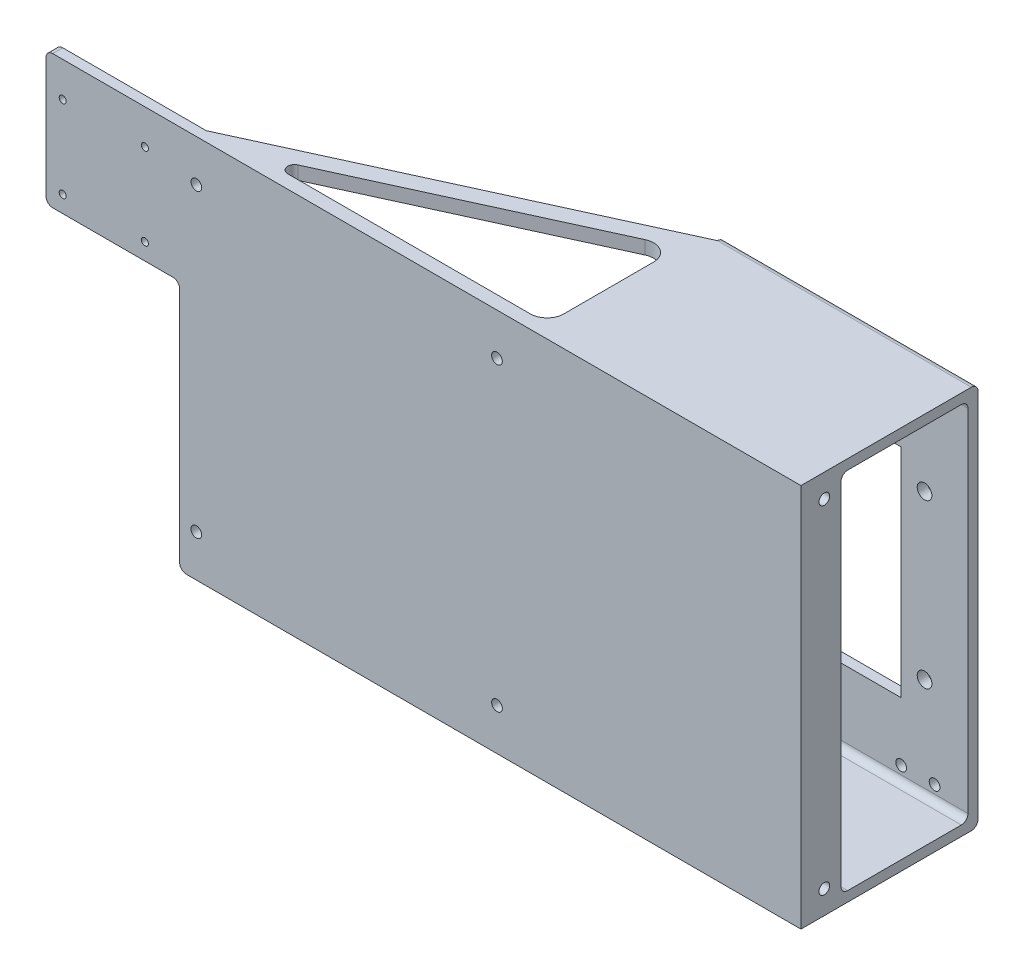
SolidWorks part; units mm, degrees
ref_plane "前视基准面" through (0, 0, 0) normal (0, 0, 1) x (1, 0, 0)
ref_plane "上视基准面" through (0, 0, 0) normal (0, 1, 0) x (1, 0, 0)
ref_plane "右视基准面" through (0, 0, 0) normal (1, 0, 0) x (0, 0, -1)
sketch "草图2" plane through (0, 0, 0) normal (0, 0, 1) x (1, 0, 0)
  line L4 (37.2625, -42.4817) -> (86.0528, -91.2721) construction
  line L5 (23.0528, -9.4817) -> (99.0528, -9.4817)
  line L6 (23.0528, -9.4817) -> (23.0528, -124.4817)
  line L7 (23.0528, -124.4817) -> (99.0528, -124.4817)
  line L8 (99.0528, -9.4817) -> (99.0528, -124.4817)
  line L9 (86.0528, -42.4817) -> (37.2625, -91.2721) construction
  circle A0 centre (86.0528, -91.2721) radius 2.2
  circle A1 centre (86.0528, -42.4817) radius 2.2
  circle A2 centre (37.2625, -42.4817) radius 2.2
  circle A3 centre (37.2625, -91.2721) radius 2.2
  circle A4 centre (89.0528, -16.9817) radius 1.6
  circle A5 centre (79.0528, -16.9817) radius 1.6
  circle A6 centre (41.0528, -16.9817) radius 1.6
  circle A7 centre (51.0528, -16.9817) radius 1.6
  circle A8 centre (41.0528, -116.9817) radius 1.6
  circle A9 centre (51.0528, -116.9817) radius 1.6
  circle A10 centre (79.0528, -116.9817) radius 1.6
  circle A11 centre (89.0528, -116.9817) radius 1.6
  point P12 (64.3101, -80.4099)
  dimension "D4" = 90
  dimension "D5" = 13
  dimension "D6" = 33
  dimension "D7" = 69
  dimension "D8" = 3.2
  dimension "D3" = 69
  dimension "D9" = 10
  dimension "D10" = 7.5
  dimension "D11" = 4.4
  dimension "D12" = 4.4
  dimension "D13" = 4.4
  dimension "D14" = 4.4
  dimension "D18" = 100
  dimension "D1" = 115
  dimension "D2" = 76
  dimension "D15" = 2
  dimension "D16" = 2
  dimension "D17" = 2
extrude "凸台-拉伸1" add sketch "草图2" along normal blind 3
sketch "草图3" plane through (23.0528, 0, 0) normal (-1, 0, 0) x (0, 0, 1)
  line L0 (0, -9.4817) -> (0, -124.4817) construction
  line L1 (0, -9.4817) -> (53, -9.4817)
  line L2 (0, -9.4817) -> (0, -12.4817)
  line L3 (0, -12.4817) -> (50, -12.4817)
  line L8 (50, -12.4817) -> (50, -121.4817)
  line L9 (53, -124.4817) -> (0, -124.4817)
  line L11 (50, -121.4817) -> (0, -121.4817)
  line L12 (0, -124.4817) -> (0, -121.4817)
  line L13 (53, -124.4817) -> (53, -9.4817)
  dimension "D1" = 115
  dimension "D2" = 3
  dimension "D4" = 50
extrude "凸台-拉伸2" add sketch "草图3" against normal blind 76
sketch "草图4" plane through (23.0528, 0, 0) normal (-1, 0, 0) x (0, 0, 1)
  line L0 (3, -12.4817) -> (50, -12.4817) construction
  line L1 (3, -12.4817) -> (50, -12.4817)
  line L2 (3, -12.4817) -> (3, -121.4817)
  line L3 (3, -121.4817) -> (50, -121.4817)
  line L4 (50, -12.4817) -> (50, -121.4817)
  line L5 (3, -12.4817) -> (3, -121.4817) construction
extrude "凸台-拉伸3" add sketch "草图4" against normal blind 3
sketch "草图5" plane through (99.0528, 0, 0) normal (1, 0, 0) x (0, 0, -1)
  line L0 (-53, -124.4817) -> (0, -124.4817) construction
  line L1 (-53, -9.4817) -> (-41, -9.4817)
  line L2 (-53, -9.4817) -> (-53, -124.4817)
  line L3 (-53, -124.4817) -> (-41, -124.4817)
  line L4 (-41, -9.4817) -> (-41, -124.4817)
  circle A0 centre (-46, -117.4817) radius 1.6
  circle A1 centre (-46, -16.4817) radius 1.6
  dimension "D2" = 5
  dimension "D3" = 7
  dimension "D4" = 5
  dimension "D5" = 7
  dimension "D1" = 12
extrude "凸台-拉伸4" add sketch "草图5" against normal blind 3
fillet "圆角1" radius 2 8 edges at (97.5528, -121.4817, 41) (97.5528, -12.4817, 41) (61.0528, -12.4817, 50) (61.0528, -121.4817, 50) (62.5528, -121.4817, 3) (61.0528, -124.4817, 0) (61.0528, -9.4817, 0) (62.5528, -12.4817, 3)
sketch "草图6" plane through (23.0528, 0, 0) normal (-1, 0, 0) x (0, 0, 1)
  line L1 (53, -9.4817) -> (50, -9.4817)
  line L2 (53, -9.4817) -> (53, -124.4817)
  line L3 (53, -124.4817) -> (50, -124.4817)
  line L4 (50, -9.4817) -> (50, -124.4817)
  line L5 (53, -124.4817) -> (2, -124.4817) construction
  dimension "D1" = 3
  dimension "D2" = 115
  dimension "D3" = 0
extrude "凸台-拉伸5" add sketch "草图6" along normal blind 110
sketch "草图7" plane through (0, 0, 50) normal (0, 0, -1) x (-1, 0, 0)
  line L0 (86.9472, -9.4817) -> (86.9472, -124.4817) construction
  line L1 (86.9472, -9.4817) -> (-23.0528, -9.4817) construction
  circle A0 centre (81.9472, -21.9817) radius 1.6
  circle A1 centre (81.9472, -111.9817) radius 1.6
  circle A2 centre (-8.0528, -21.9817) radius 1.6
  circle A3 centre (-8.0528, -111.9817) radius 1.6
  point P32 (0, 0)
  point P33 (0, 0)
  dimension "D1" = 5
  dimension "D2" = 12.5
  dimension "D5" = 90
  dimension "D6" = 90
  dimension "D3" = 2
  dimension "D4" = 2
extrude "切除-拉伸1" cut sketch "草图7" against normal blind 110
sketch "草图8" plane through (0, 0, 0) normal (0, 0, -1) x (-1, 0, 0)
  line L0 (-99.0528, -122.4817) -> (-99.0528, -11.4817) construction
  line L1 (-79.0528, -34.4817) -> (-48.0528, -34.4817)
  line L2 (-79.0528, -34.4817) -> (-79.0528, -99.4817)
  line L3 (-79.0528, -99.4817) -> (-48.0528, -99.4817)
  line L4 (-48.0528, -34.4817) -> (-48.0528, -99.4817)
  line L5 (-23.0528, -11.4817) -> (-23.0528, -122.4817) construction
  line L6 (-23.0528, -11.4817) -> (-99.0528, -11.4817) construction
  line L7 (-99.0528, -122.4817) -> (-23.0528, -122.4817) construction
  dimension "D1" = 20
  dimension "D2" = 25
  dimension "D3" = 23
  dimension "D4" = 23
extrude "切除-拉伸2" cut sketch "草图8" against normal blind 3
sketch "草图9" plane through (0, -124.4817, 0) normal (0, -1, 0) x (-1, 0, 0)
  line L0 (-23.0528, -2) -> (81.9472, -50)
  line L1 (81.9472, -50) -> (-23.0528, -50)
  line L2 (-23.0528, -50) -> (-23.0528, -2)
extrude "凸台-拉伸6" add sketch "草图9" against normal blind 4
sketch "草图10" plane through (0, -9.4817, 0) normal (0, 1, 0) x (1, 0, 0)
  line L0 (23.0528, -2) -> (-81.9472, -50)
  line L1 (-81.9472, -50) -> (23.0528, -50)
  line L2 (23.0528, -50) -> (23.0528, -2)
extrude "凸台-拉伸7" add sketch "草图10" against normal blind 4
sketch "草图11" plane through (0, -124.4817, 0) normal (0, -1, 0) x (-1, 0, 0)
  line L0 (58.548, -49) -> (-14.0528, -49)
  line L1 (-19.0528, -44) -> (-19.0528, -17.1096)
  line L2 (-11.974, -12.5623) -> (59.3795, -45.1811)
  line L3 (-99.0528, -53) -> (86.9472, -53) construction
  line L4 (-99.0528, -53) -> (-99.0528, -2) construction
  line L5 (81.9472, -50) -> (-23.0528, -2) construction
  arc A0 (-14.0528, -49) -> (-19.0528, -44) centre (-14.0528, -44) cw
  arc A1 (-19.0528, -17.1096) -> (-11.974, -12.5623) centre (-14.0528, -17.1096) cw
  arc A2 (58.548, -49) -> (59.3795, -45.1811) centre (58.548, -47) ccw
  dimension "D4" = 5
  dimension "D5" = 2
  dimension "D1" = 4
  dimension "D2" = 80
  dimension "D3" = 5
extrude "切除-拉伸3" cut sketch "草图11" against normal blind 124
sketch "草图16" plane through (-86.9472, 0, 0) normal (-1, 0, 0) x (0, 0, 1)
  line L0 (53, -124.4817) -> (53, -9.4817) construction
  line L1 (50, -9.4817) -> (53, -9.4817)
  line L2 (50, -9.4817) -> (50, -49.4817)
  line L3 (50, -49.4817) -> (53, -49.4817)
  line L4 (53, -9.4817) -> (53, -49.4817)
  dimension "D1" = 40
extrude "凸台-拉伸10" add sketch "草图16" along normal blind 40
sketch "草图17" plane through (0, 0, 50) normal (0, 0, -1) x (-1, 0, 0)
  line L4 (126.9472, -9.4817) -> (126.9472, -49.4817) construction
  line L6 (126.9472, -49.4817) -> (86.9472, -49.4817) construction
  circle A4 centre (121.9472, -44.4817) radius 1.05
  circle A5 centre (121.9472, -19.8817) radius 1.05
  circle A26 centre (97.3472, -19.8817) radius 1.05
  circle A29 centre (97.3472, -44.4817) radius 1.05
  point P32 (29.0087, 124.7414)
  point P33 (29.0087, 124.7414)
  dimension "D2" = 5
  dimension "D15" = 24.6
  dimension "D16" = 2.1
  dimension "D7" = 2.1
  dimension "D8" = 2.1
  dimension "D4" = 5
  dimension "D3" = 24.6
extrude "切除-拉伸5" cut sketch "草图17" against normal blind 40
fillet "圆角5" radius 2 4 edges at (-126.9472, -9.4817, 51.5) (-126.9472, -49.4817, 51.5) (-86.9472, -49.4817, 51.5) (-86.9472, -124.4817, 51.5)
sketch "草图18" plane through (23.0528, 0, 0) normal (-1, 0, 0) x (0, 0, 1)
  line L0 (0, -11.4817) -> (0, -122.4817) construction
  line L1 (8, -23.4817) -> (30, -23.4817)
  line L2 (8, -23.4817) -> (8, -110.4817)
  line L3 (8, -110.4817) -> (30, -110.4817)
  line L4 (30, -23.4817) -> (30, -110.4817)
  line L5 (50, -13.4817) -> (50, -120.4817) construction
  line L6 (50, -13.4817) -> (2, -13.4817) construction
  line L7 (50, -120.4817) -> (2, -120.4817) construction
  dimension "D1" = 8
  dimension "D2" = 20
  dimension "D3" = 10
  dimension "D4" = 10
extrude "切除-拉伸6" cut sketch "草图18" against normal blind 4 contours L1 L4 L3 L2
